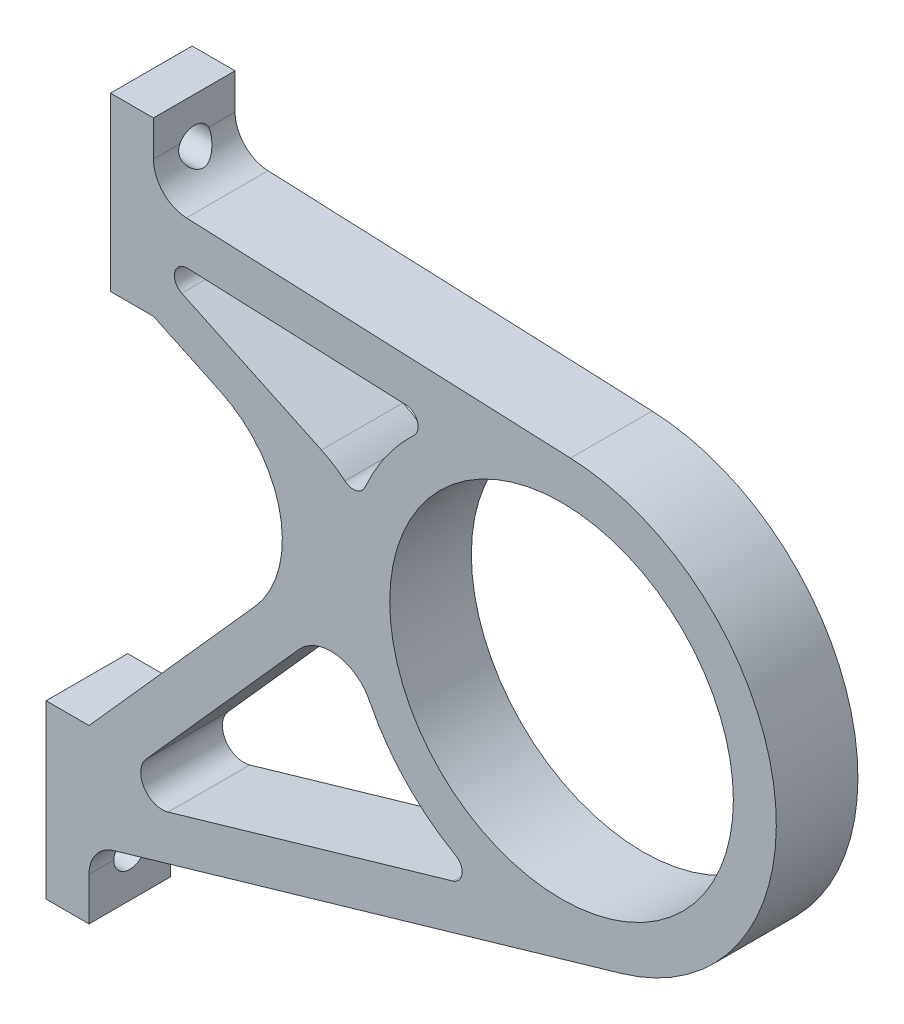
SolidWorks part; units mm, degrees
material "6061 Alloy"
ref_plane "Front Plane" through (0, 0, 0) normal (0, 0, 1) x (1, 0, 0)
ref_plane "Top Plane" through (0, 0, 0) normal (0, 1, 0) x (1, 0, 0)
ref_plane "Right Plane" through (0, 0, 0) normal (1, 0, 0) x (0, 0, -1)
sketch "Sketch1" plane through (0, 0, 0) normal (0, 0, 1) x (1, 0, 0)
  line L0 (-133.35, 88.9) -> (-133.35, 38.1)
  line L1 (-133.35, 38.1) -> (-120.65, 38.1)
  line L2 (-133.35, 88.9) -> (-120.65, 88.9)
  line L3 (-120.65, 88.9) -> (-120.65, 68.58)
  line L4 (-120.65, 68.58) -> (2.6424, 63.445)
  line L5 (-152.4, -76.2) -> (-139.7, -76.2)
  line L6 (-152.4, -76.2) -> (-152.4, -127)
  line L7 (-152.4, -127) -> (-139.7, -127)
  line L8 (-139.7, -127) -> (-139.7, -106.68)
  line L9 (-139.7, -106.68) -> (17.7044, -60.982)
  line L10 (-120.65, 38.1) -> (-100.7551, 28.7158)
  line L11 (-139.7, -76.2) -> (-90.6011, -21.1288)
  line L12 (-46.0374, 52.7615) -> (-110.4951, 55.4461)
  line L13 (-112.2791, 48.1935) -> (-70.9856, 28.7158)
  line L14 (-77.621, -25.6539) -> (-122.808, -76.3375)
  line L15 (-116.2978, -86.6614) -> (-32.1185, -62.2223)
  arc A0 (-56.7845, -28.4212) -> (-31.3026, -55.2485) centre (0, 0) ccw
  circle A1 centre (0, 0) radius 50.8
  arc A2 (-90.6011, -21.1288) -> (-100.7551, 28.7158) centre (-114.3, 0) ccw
  arc A3 (-64.0429, 24.2554) -> (-70.9856, 28.7158) centre (-84.5305, 0) ccw
  arc A4 (-110.4951, 55.4461) -> (-112.2791, 48.1935) centre (-110.6537, 51.6394) ccw
  arc A6 (-122.808, -76.3375) -> (-116.2978, -86.6614) centre (-118.0683, -80.5632) ccw
  arc A7 (17.7044, -60.982) -> (2.6424, 63.445) centre (0, 0) ccw
  arc A8 (-43.5811, 46.1837) -> (-58.0985, 25.6283) centre (0, 0) ccw
  arc A9 (-46.0374, 52.7615) -> (-43.5811, 46.1837) centre (-46.196, 48.9548) cw
  arc A10 (-64.0429, 24.2554) -> (-58.0985, 25.6283) centre (-61.5844, 27.166) ccw
  arc A11 (-32.1185, -62.2223) -> (-31.3026, -55.2485) centre (-33.1808, -58.5634) ccw
  arc A12 (-77.621, -25.6539) -> (-56.7845, -28.4212) centre (-68.1415, -34.1055) cw
  point P44 (-35.9531, 52.3414)
  dimension "D1" = 12.7
  dimension "D2" = 101.6
  dimension "D13" = 63.5
  dimension "D14" = 31.75
  dimension "D17" = 3.81
  dimension "D18" = 31.75
  dimension "D21" = 6.35
  dimension "D22" = 3.81
  dimension "D23" = 3.81
  dimension "D24" = 12.7
  dimension "D3" = 50.8
  dimension "D4" = 12.7
  dimension "D5" = 20.32
  dimension "D6" = 133.35
  dimension "D7" = 152.4
  dimension "D8" = 12.7
  dimension "D9" = 50.8
  dimension "D10" = 20.32
  dimension "D11" = 88.9
  dimension "D12" = 127
  dimension "D15" = 12.7
  dimension "D16" = 12.7
  dimension "D19" = 12.7
  dimension "D20" = 12.7
extrude "Boss-Extrude1" add sketch "Sketch1" along normal blind 24.13 contours A1
fillet "Fillet1" radius 10.16 2 edges at (-139.7, -106.68, 12.065) (-120.65, 68.58, 12.065)
sketch "Sketch2" plane through (-152.4, 0, 0) normal (-1, 0, 0) x (0, 0, 1)
  line L0 (24.13, 88.9) -> (0, 88.9) construction
  line L1 (24.13, -127) -> (0, -127) construction
  circle A0 centre (12.065, -114.3) radius 4.7625
  circle A1 centre (12.065, 76.2) radius 4.7625
  point P6 (12.065, 88.9)
  dimension "D1" = 9.525
  dimension "D2" = 12.7
  dimension "D3" = 12.7
extrude "Cut-Extrude1" cut sketch "Sketch2" against normal through all
